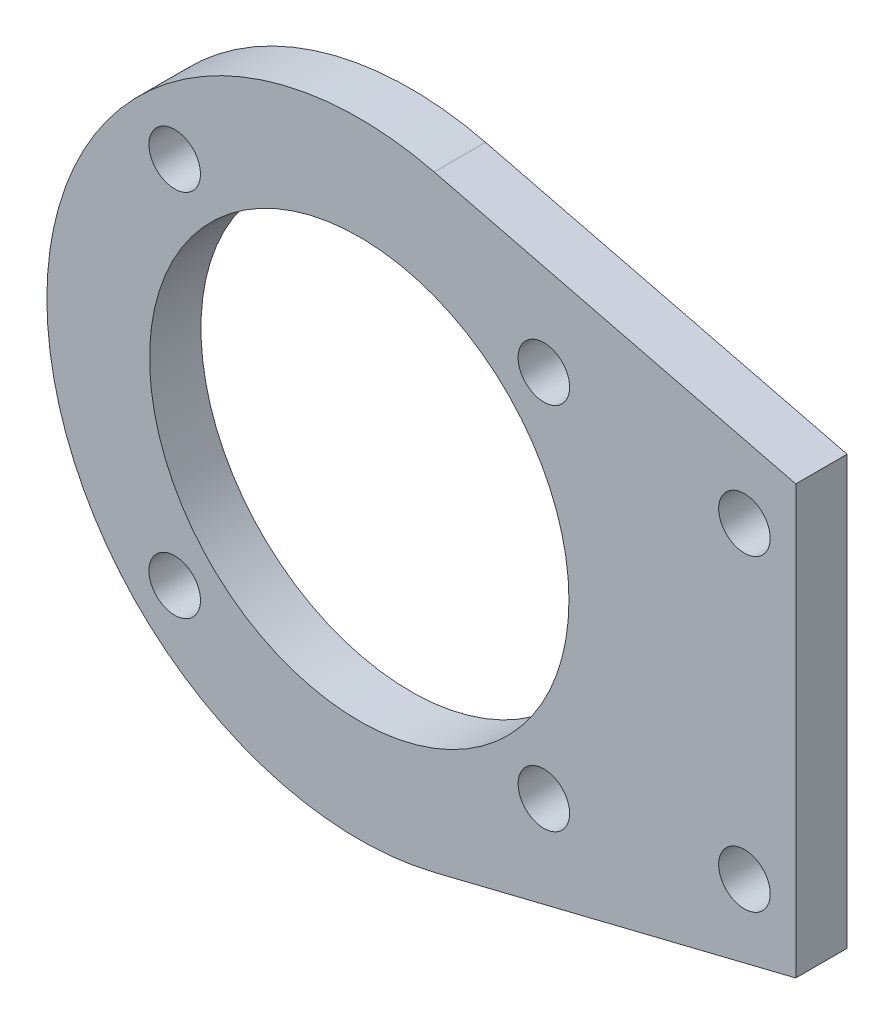
SolidWorks part; units mm, degrees
material "Thornel Mat VMA"
ref_plane "前视基准面" through (0, 0, 0) normal (0, 0, 1) x (1, 0, 0)
ref_plane "上视基准面" through (0, 0, 0) normal (0, 1, 0) x (1, 0, 0)
ref_plane "右视基准面" through (0, 0, 0) normal (1, 0, 0) x (0, 0, -1)
sketch "草图1" plane through (0, 0, 0) normal (0, 0, 1) x (1, 0, 0)
  line L0 (25.5, 12.5) -> (25.5, -12.5)
  line L1 (0, 0) -> (25.5, 0) construction
  line L2 (25.5, 12.5) -> (4.3762, 17.7175)
  line L3 (25.5, -12.5) -> (4.3762, -17.7175)
  circle A0 centre (0, 0) radius 12.25
  arc A1 (4.3762, 17.7175) -> (4.3762, -17.7175) centre (0, 0) ccw
  circle A2 centre (0, 0) radius 18.25 construction
  dimension "D1" = 24.5
  dimension "D3" = 25.5
  dimension "D4" = 25
  dimension "D2" = 6
extrude "凸台-拉伸1" add sketch "草图1" along normal blind 3
sketch "草图2" plane through (0, 0, 3) normal (0, 0, 1) x (1, 0, 0)
  line L0 (-15.25, 0) -> (0, 0) construction
  line L1 (0, 0) -> (-10.7834, 10.7834) construction
  circle A0 centre (0, 0) radius 15.25 construction
  arc A1 (4.3762, 17.7175) -> (4.3762, -17.7175) centre (0, 0) ccw construction
  circle A2 centre (-10.7834, 10.7834) radius 1.505
  circle A3 centre (10.7834, 10.7834) radius 1.505
  circle A4 centre (10.7834, -10.7834) radius 1.505
  circle A5 centre (-10.7834, -10.7834) radius 1.505
  point P9 (10.4288, -10.4308)
  point P10 (0, 0)
  point P11 (0, 0)
  point P18 (0, 0)
  point P19 (0, 0)
  dimension "D1" = 3
  dimension "D3" = 3.01
  dimension "D2" = 45
  dimension "D4" = 4
extrude "切除-拉伸1" cut sketch "草图2" against normal blind 32
sketch "草图4" plane through (0, 0, 3) normal (0, 0, 1) x (1, 0, 0)
  line L0 (22.5, 9) -> (22.5, -9) construction
  line L1 (0, 0) -> (22.5, 0) construction
  line L2 (25.5, -12.5) -> (25.5, 12.5) construction
  circle A0 centre (22.5, -9) radius 1.505
  circle A1 centre (22.5, 9) radius 1.505
  dimension "D3" = 3.01
  dimension "D1" = 3
  dimension "D2" = 18
extrude "切除-拉伸2" cut sketch "草图4" against normal mid plane 6
